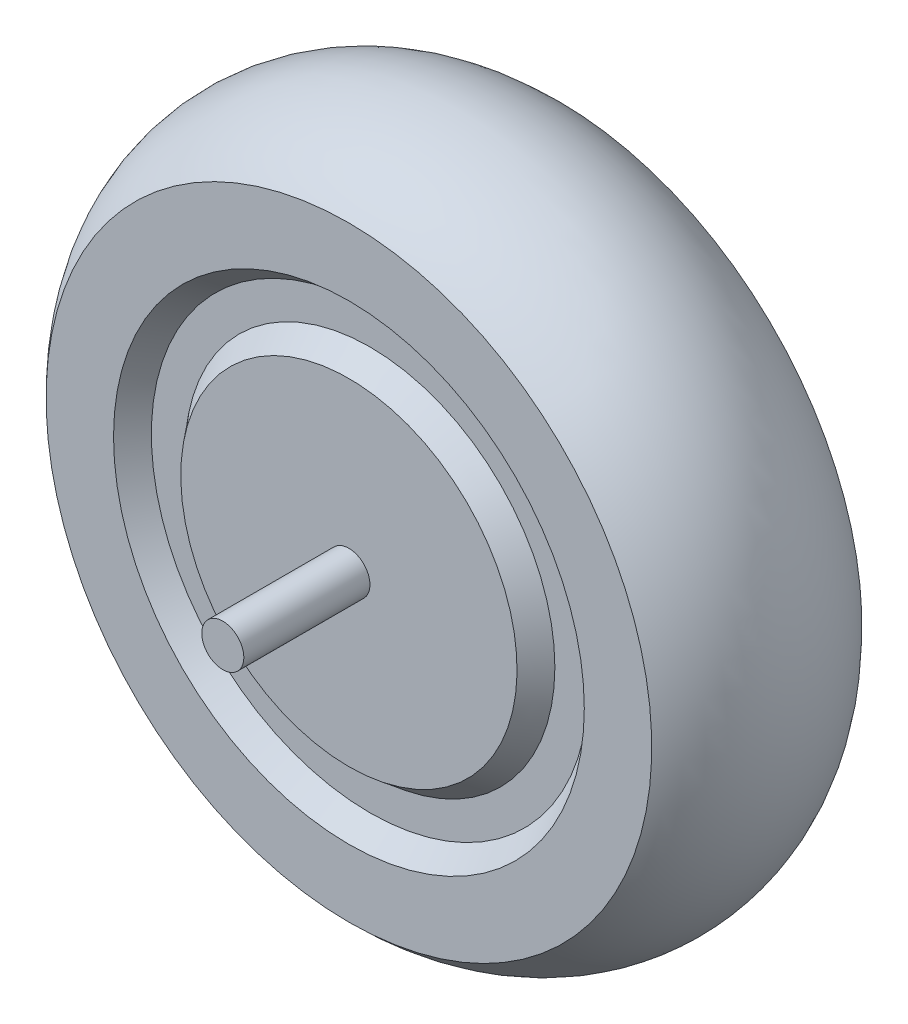
SolidWorks part; units mm, degrees
material "Caucho"
ref_plane "Alzado" through (0, 0, 0) normal (0, 0, 1) x (1, 0, 0)
ref_plane "Planta" through (0, 0, 0) normal (0, 1, 0) x (1, 0, 0)
ref_plane "Vista lateral" through (0, 0, 0) normal (1, 0, 0) x (0, 0, -1)
sketch "Croquis1" plane through (0, 0, 0) normal (1, 0, 0) x (0, 0, -1)
  line L0 (-40, 0) -> (40, 0)
  line L1 (-40, 0) -> (-40, -5)
  line L2 (-40, -5) -> (-10, -5)
  line L3 (-10, -5) -> (-10, -40)
  line L4 (-10, -40) -> (-5, -44)
  line L5 (-5, -44) -> (-5, -52)
  line L6 (-5, -52) -> (-10, -56)
  line L7 (-10, -40) -> (40, -40) construction
  line L8 (35, -44) -> (-5, -44) construction
  line L9 (-5, -52) -> (35, -52) construction
  line L10 (40, -56) -> (-10, -56) construction
  line L11 (35, -52) -> (40, -56)
  line L12 (35, -44) -> (35, -52)
  line L13 (40, -40) -> (35, -44)
  line L14 (40, 0) -> (40, -40)
  line L15 (15, -40) -> (15, -47.55) construction
  line L16 (-10, -56) -> (-10, -72.0449)
  line L17 (40, -56) -> (40, -72.0449)
  line L18 (40, -72.0449) -> (-10, -72.0449) construction
  line L19 (-102.411, 0) -> (124.2068, 0) construction
  arc A1 (-10, -72.0449) -> (40, -72.0449) centre (15, -47.55) ccw
  point P12 (15, -52)
  point P13 (15, -44)
  point P19 (0, 0)
  point P23 (15, -82.55)
  dimension "D2" = 5
  dimension "D5" = 82.55
  dimension "D3" = 35
  dimension "D1" = 80
  dimension "D4" = 50
  dimension "D6" = 40
  dimension "D7" = 4
  dimension "D8" = 4
  dimension "D9" = 5
  dimension "D10" = 8
revolve "Revolución1" add sketch "Croquis1" angle 360 about L0
